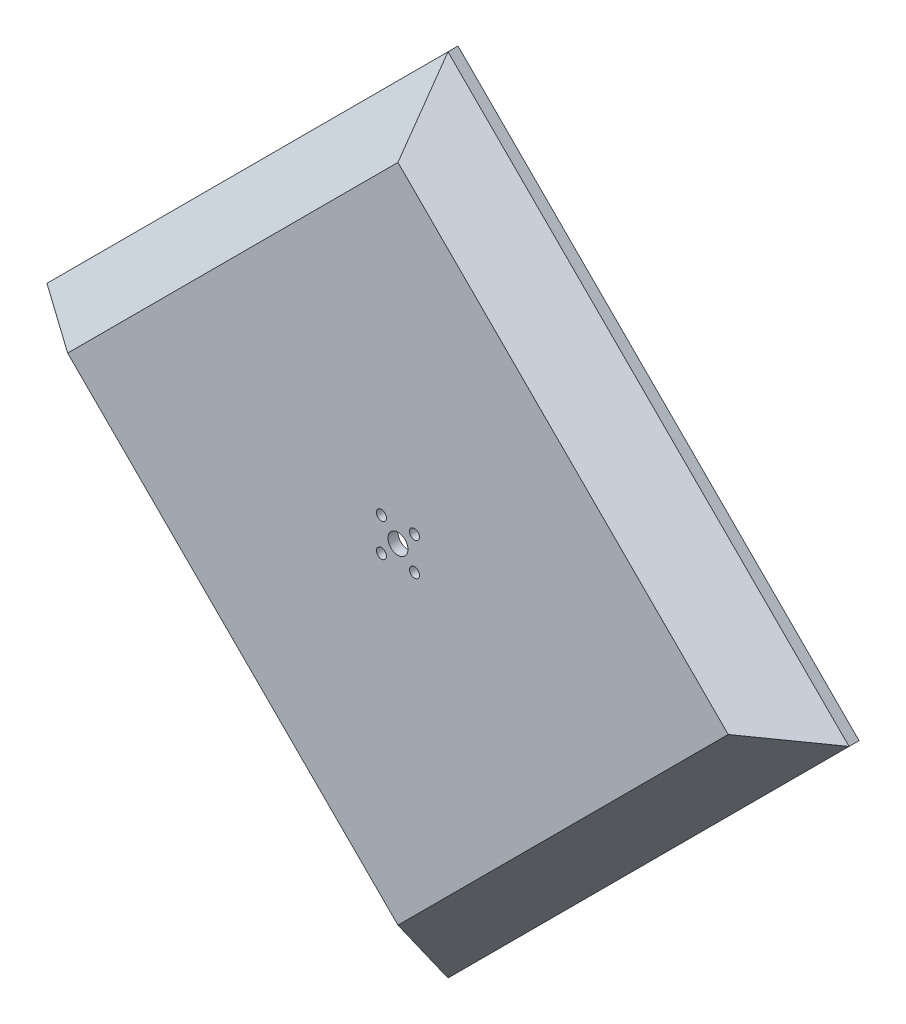
SolidWorks part; units mm, degrees
ref_plane "前视基准面" through (0, 0, 0) normal (0, 0, 1) x (1, 0, 0)
ref_plane "上视基准面" through (0, 0, 0) normal (0, 1, 0) x (1, 0, 0)
ref_plane "右视基准面" through (0, 0, 0) normal (1, 0, 0) x (0, 0, -1)
sketch "草图1" plane through (0, 0, 0) normal (0, 0, 1) x (1, 0, 0)
  line L1 (85, -85) -> (-85, -85)
  line L2 (85, -85) -> (85, 85)
  line L3 (85, 85) -> (-85, 85)
  line L4 (-85, -85) -> (-85, 85)
  line L5 (85, -85) -> (-85, 85) construction
  line L6 (85, 85) -> (-85, -85) construction
  point P0 (0, 0)
  dimension "D1" = 170
  dimension "D2" = 170
extrude "凸台-拉伸1" add sketch "草图1" along normal blind 3
sketch "草图3" plane through (0, 0, 0) normal (0, 0, -1) x (-1, 0, 0)
  line L1 (4.95, -4.95) -> (-4.95, -4.95) construction
  line L2 (4.95, -4.95) -> (4.95, 4.95) construction
  line L3 (4.95, 4.95) -> (-4.95, 4.95) construction
  line L4 (-4.95, -4.95) -> (-4.95, 4.95) construction
  line L5 (4.95, -4.95) -> (-4.95, 4.95) construction
  line L6 (4.95, 4.95) -> (-4.95, -4.95) construction
  circle A0 centre (0, 0) radius 3
  circle A1 centre (4.95, 4.95) radius 1.5
  circle A2 centre (-4.95, 4.95) radius 1.5
  circle A3 centre (-4.95, -4.95) radius 1.5
  circle A4 centre (4.95, -4.95) radius 1.5
  point P0 (0, 0)
  dimension "D1" = 6
  dimension "D2" = 3
  dimension "D3" = 3
  dimension "D4" = 3
  dimension "D5" = 3
  dimension "D6" = 9.9
  dimension "D7" = 9.9
extrude "切除-拉伸1" cut sketch "草图3" against normal through all
fillet "圆角1" radius 2 4 edges at (85, -85, 1.5) (85, 85, 1.5) (-85, -85, 1.5) (-85, 85, 1.5)
sketch "草图4" plane through (0, 0, 0) normal (0, 0, -1) x (-1, 0, 0)
  line L0 (0, 0) -> (22.2376, 22.2376) construction
  line L1 (60.1041, -60.1041) -> (-60.1041, 60.1041)
  line L2 (35.2082, -85) -> (85, -35.2082)
  line L3 (-85, 35.2082) -> (-35.2082, 85)
  line L4 (-85, 83) -> (-85, -83)
  line L5 (-83, -85) -> (83, -85)
  line L6 (85, -83) -> (85, 83)
  line L7 (83, 85) -> (-83, 85)
  line L8 (-85, 83) -> (-85, -83)
  line L9 (-83, -85) -> (83, -85)
  line L10 (85, -83) -> (85, 83)
  line L11 (83, 85) -> (-83, 85)
  line L12 (-60.1041, -60.1041) -> (60.1041, 60.1041)
  line L13 (-60.1041, -60.1041) -> (-85, -36.1123)
  line L14 (-60.1041, -60.1041) -> (-34.2699, -85)
  line L15 (60.1041, 60.1041) -> (85, 34.2699)
  line L16 (60.1041, 60.1041) -> (36.1123, 85)
  arc A4 (-85, -83) -> (-83, -85) centre (-83, -83) ccw
  arc A5 (83, -85) -> (85, -83) centre (83, -83) ccw
  arc A6 (85, 83) -> (83, 85) centre (83, 83) ccw
  arc A7 (-83, 85) -> (-85, 83) centre (-83, 83) ccw
  arc A8 (-85, -83) -> (-83, -85) centre (-83, -83) ccw
  arc A9 (83, -85) -> (85, -83) centre (83, -83) ccw
  arc A10 (85, 83) -> (83, 85) centre (83, 83) ccw
  arc A11 (-83, 85) -> (-85, 83) centre (-83, 83) ccw
  line M18 (-85, 83) -> (-85, -83)
  line M20 (-83, -85) -> (83, -85)
  arc M21 (83, -85) -> (85, -83) centre (83, -83) ccw
  line M22 (85, -83) -> (85, 83)
  line M24 (83, 85) -> (-83, 85)
  arc M25 (-83, 85) -> (-85, 83) centre (-83, 83) ccw
  dimension "D2" = 85
  dimension "D3" = 85
  dimension "D1" = 0
extrude "切除-拉伸2" cut sketch "草图4" against normal blind 10 contours L3 M18 M24 M25 | L2 M20 M21 M22
sketch "草图5" plane through (0, 0, 0) normal (0, 0, -1) x (-1, 0, 0)
  line L0 (-35.2082, 85) -> (24.3101, 144.5183)
  line L1 (24.3101, 144.5183) -> (144.5183, 24.3101)
  line L2 (0, 0) -> (-60.1041, 60.1041) construction
  line L3 (-85, 35.2082) -> (-35.2082, 85) construction
  line L4 (0, 0) -> (84.4142, 84.4142) construction
  line L5 (-85, -83) -> (-85, 35.2082)
  line L6 (-144.5183, -24.3101) -> (-24.3101, -144.5183)
  line L7 (-85, 35.2082) -> (-144.5183, -24.3101)
  line L8 (85, -35.2082) -> (144.5183, 24.3101)
  line L9 (35.2082, -85) -> (-24.3101, -144.5183)
  line L11 (83, 85) -> (-35.2082, 85)
  line L12 (-35.2082, 85) -> (-85, 35.2082)
  line L13 (-85, 35.2082) -> (-85, -83)
  line L14 (-83, -85) -> (35.2082, -85)
  line L15 (35.2082, -85) -> (85, -35.2082)
  line L16 (85, -35.2082) -> (85, 83)
  line L17 (83, 85) -> (-35.2082, 85)
  line L18 (-35.2082, 85) -> (-85, 35.2082)
  line L19 (-85, 35.2082) -> (-85, -83)
  line L20 (-83, -85) -> (35.2082, -85)
  line L21 (35.2082, -85) -> (85, -35.2082)
  line L22 (85, -35.2082) -> (85, 83)
  arc A0 (85, 83) -> (83, 85) centre (83, 83) ccw construction
  arc A3 (-85, -83) -> (-83, -85) centre (-83, -83) ccw
  arc A4 (85, 83) -> (83, 85) centre (83, 83) ccw
  arc A5 (-85, -83) -> (-83, -85) centre (-83, -83) ccw
  arc A6 (85, 83) -> (83, 85) centre (83, 83) ccw
  point P25 (-84.4142, -84.4142)
  dimension "D1" = 0
sketch "草图6" plane through (0, 0, 0) normal (0, 0, -1) x (-1, 0, 0)
  line L0 (-60.1041, -60.1041) -> (60.1041, 60.1041)
  line L1 (0, 0) -> (84.4142, 84.4142) construction
  line L2 (0, 0) -> (-32.158, 32.158)
  line L3 (0, 0) -> (-60.1041, 60.1041) construction
  line L4 (60.1041, 60.1041) -> (35.2082, 85)
  line L5 (60.1041, 60.1041) -> (85, 35.2082)
  line L6 (83, 85) -> (-35.2082, 85)
  line L7 (-35.2082, 85) -> (-85, 35.2082)
  line L8 (-85, 35.2082) -> (-85, -83)
  line L9 (-83, -85) -> (35.2082, -85)
  line L10 (35.2082, -85) -> (85, -35.2082)
  line L11 (85, -35.2082) -> (85, 83)
  line L12 (83, 85) -> (-35.2082, 85)
  line L13 (-35.2082, 85) -> (-85, 35.2082)
  line L14 (-85, 35.2082) -> (-85, -83)
  line L15 (-83, -85) -> (35.2082, -85)
  line L16 (35.2082, -85) -> (85, -35.2082)
  line L17 (85, -35.2082) -> (85, 83)
  line L18 (-60.1041, -60.1041) -> (-35.2082, -85)
  line L19 (-60.1041, -60.1041) -> (-85, -35.2082)
  arc A2 (-85, -83) -> (-83, -85) centre (-83, -83) ccw
  arc A3 (85, 83) -> (83, 85) centre (83, 83) ccw
  arc A4 (-85, -83) -> (-83, -85) centre (-83, -83) ccw
  arc A5 (85, 83) -> (83, 85) centre (83, 83) ccw
  line M18 (83, 85) -> (-35.2082, 85)
  arc M21 (-85, -83) -> (-83, -85) centre (-83, -83) ccw
  line M22 (-83, -85) -> (35.2082, -85)
  line M24 (85, -35.2082) -> (85, 83)
  arc M25 (85, 83) -> (83, 85) centre (83, 83) ccw
  dimension "D2" = 85
  dimension "D1" = 0
extrude "切除-拉伸3" cut sketch "草图6" against normal blind 3 contours L18 L19 L14 M21 M22 | L4 L5 M24 M25 M18
sketch "草图7" plane through (0, 0, 0) normal (0, 0, -1) x (-1, 0, 0)
  line L0 (-120.2082, 0) -> (0, 120.2082)
  line L1 (-35.2082, 85) -> (24.3101, 144.5183) construction
  line L2 (0, 120.2082) -> (35.2082, 85)
  line L3 (0, 0) -> (-21.4242, 21.4242)
  line L4 (0, 0) -> (-60.1041, 60.1041) construction
  line L5 (0, 0) -> (24.2164, 24.2164)
  line L6 (0, 0) -> (84.4142, 84.4142) construction
  line L7 (-120.2082, 0) -> (-85, -35.2082)
  line L8 (-85, -35.2082) -> (-35.2082, -85)
  line L9 (-35.2082, -85) -> (35.2082, -85)
  line L10 (35.2082, -85) -> (85, -35.2082)
  line L11 (85, -35.2082) -> (85, 35.2082)
  line L12 (85, 35.2082) -> (35.2082, 85)
  line L13 (35.2082, 85) -> (-35.2082, 85)
  line L14 (-35.2082, 85) -> (-85, 35.2082)
  line L15 (-85, 35.2082) -> (-85, -35.2082)
  line L16 (-85, -35.2082) -> (-35.2082, -85)
  line L17 (-35.2082, -85) -> (35.2082, -85)
  line L18 (35.2082, -85) -> (85, -35.2082)
  line L19 (85, -35.2082) -> (85, 35.2082)
  line L20 (85, 35.2082) -> (35.2082, 85)
  line L21 (35.2082, 85) -> (-35.2082, 85)
  line L22 (-35.2082, 85) -> (-85, 35.2082)
  line L23 (-85, 35.2082) -> (-85, -35.2082)
  line L24 (85, 35.2082) -> (85, -35.2082)
  line L25 (120.2082, 0) -> (85, 35.2082)
  line L26 (35.2082, -85) -> (-35.2082, -85)
  line L27 (0, -120.2082) -> (-35.2082, -85)
  line L28 (0, -120.2082) -> (120.2082, 0)
  point P22 (-60.1041, 60.1041)
  line M19 (-35.2082, -85) -> (35.2082, -85)
  line M21 (85, -35.2082) -> (85, 35.2082)
  line M23 (35.2082, 85) -> (-35.2082, 85)
  line M25 (-85, 35.2082) -> (-85, -35.2082)
  dimension "D1" = 0
extrude "凸台-拉伸4" add sketch "草图7" against normal blind 3 contours L0 L7 M25 | L2 L0 M23 | L27 L28 M19 | L28 L25 M21
sketch "草图8" plane through (-60.1041, 60.1041, 0) normal (-0.7071, 0.7071, 0) x (0, 0, 1)
  line L0 (0, 85) -> (-15, 85)
  line L1 (-15, 85) -> (0, 70)
  line L2 (0, -85) -> (0, 85) construction
  line L3 (0, 70) -> (0, 73)
  line L4 (0, 73) -> (-12, 85)
  line M3 (0, 85) -> (0, -85)
  dimension "D1" = 15
  dimension "D2" = 15
  dimension "D3" = 3
  dimension "D4" = 3
extrude "凸台-拉伸5" add sketch "草图8" against normal up to vertex (170 mm away) contours L4 L0 L1 M3
pattern_circular "阵列(圆周)1" count 4 over 360 about axis through (0, 0, 0) along (0, 0, 1) of "凸台-拉伸5"
sketch "草图9" plane through (60.1041, 60.1041, 0) normal (0.7071, 0.7071, 0) x (0, 0, -1)
  line L0 (-3, 85) -> (12, 85)
  line L1 (12, 85) -> (-3, 70)
  line L2 (-3, 85) -> (-3, -85) construction
  line L3 (-3, 70) -> (-3, 85)
extrude "切除-拉伸4" cut sketch "草图9" against normal blind 179
pattern_circular "阵列(圆周)2" count 4 over 360 of "切除-拉伸4"
